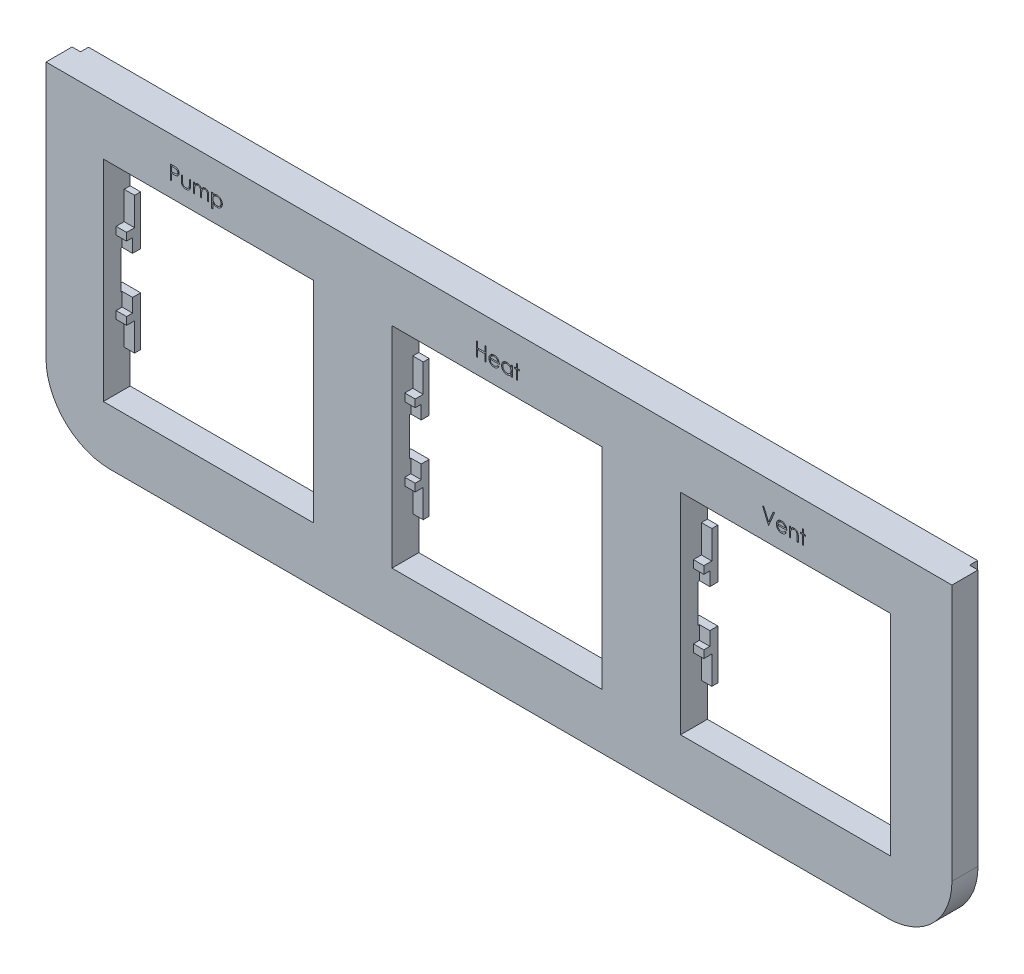
SolidWorks part; units mm, degrees
ref_plane "Спереди" through (0, 0, 0) normal (0, 0, 1) x (1, 0, 0)
ref_plane "Сверху" through (0, 0, 0) normal (0, 1, 0) x (1, 0, 0)
ref_plane "Справа" through (0, 0, 0) normal (1, 0, 0) x (0, 0, -1)
sketch "Эскиз1" plane through (0, 0, 0) normal (0, 0, 1) x (1, 0, 0)
  line L1 (0, 0) -> (226, 0)
  line L2 (0, 0) -> (0, 80)
  line L3 (0, 80) -> (226, 80)
  line L4 (226, 0) -> (226, 80)
  dimension "D1" = 80
  dimension "D2" = 226
extrude "Бобышка-Вытянуть1" add sketch "Эскиз1" along normal blind 6.5
sketch "Эскиз2" plane through (0, 0, 0) normal (0, 0, -1) x (-1, 0, 0)
  line L0 (-226, 80) -> (0, 80) construction
  line L1 (-223.9, 80) -> (-2.1, 80)
  line L2 (-223.9, 80) -> (-223.9, 2.1)
  line L3 (-223.9, 2.1) -> (-2.1, 2.1)
  line L4 (-2.1, 80) -> (-2.1, 2.1)
  dimension "D1" = 2.1
  dimension "D2" = 2.1
  dimension "D3" = 2.1
extrude "Бобышка-Вытянуть2" add sketch "Эскиз2" along normal blind 2
sketch "Эскиз3" plane through (0, 0, 6.5) normal (0, 0, 1) x (1, 0, 0)
  line L0 (0, 80) -> (0, 0) construction
  line L1 (66.7, 66.2) -> (14.3, 13.8) construction
  line L2 (14.3, 66.2) -> (66.7, 66.2)
  line L3 (14.3, 66.2) -> (14.3, 13.8)
  line L4 (14.3, 13.8) -> (66.7, 13.8)
  line L5 (66.7, 66.2) -> (66.7, 13.8)
  line L6 (86.3, 66.2) -> (138.7, 66.2)
  line L7 (86.3, 66.2) -> (86.3, 13.8)
  line L8 (86.3, 13.8) -> (138.7, 13.8)
  line L9 (138.7, 66.2) -> (138.7, 13.8)
  line L10 (158.3, 66.2) -> (210.7, 66.2)
  line L11 (158.3, 66.2) -> (158.3, 13.8)
  line L12 (158.3, 13.8) -> (210.7, 13.8)
  line L13 (210.7, 66.2) -> (210.7, 13.8)
  point P0 (40.5, 40)
  point P8 (40.5, 40)
  dimension "D1" = 40
  dimension "D2" = 40.5
  dimension "D3" = 52.4
  dimension "D4" = 52.4
  dimension "D5" = 3
extrude "Вырез-Вытянуть1" cut sketch "Эскиз3" against normal through all
sketch "Эскиз4" plane through (0, 0, -2) normal (0, 0, -1) x (-1, 0, 0)
  line L1 (-221.9, 76) -> (-4.1, 76)
  line L2 (-221.9, 76) -> (-221.9, 4.1)
  line L3 (-221.9, 4.1) -> (-4.1, 4.1)
  line L4 (-4.1, 76) -> (-4.1, 4.1)
  dimension "D1" = 2
  dimension "D2" = 2
  dimension "D3" = 2
  dimension "D4" = 4
extrude "Вырез-Вытянуть2" cut sketch "Эскиз4" against normal offset from surface (5.5 mm away) 3 up to face at (40.5, 40, 6.5)
sketch "Эскиз5" plane through (0, 0, 3.5) normal (0, 0, -1) x (-1, 0, 0)
  line L0 (-158.3, 13.8) -> (-210.7, 13.8) construction
  line L1 (-158.3, 66.2) -> (-158.3, 13.8) construction
  line L2 (-210.7, 66.2) -> (-158.3, 66.2) construction
  line L3 (-210.7, 13.8) -> (-210.7, 66.2) construction
  line L4 (-158.3, 13.8) -> (-210.7, 13.8)
  line L5 (-158.3, 66.2) -> (-158.3, 13.8)
  line L6 (-210.7, 66.2) -> (-158.3, 66.2)
  line L7 (-210.7, 13.8) -> (-210.7, 66.2)
  line L8 (-86.3, 13.8) -> (-138.7, 13.8)
  line L9 (-212.7, 68.2) -> (-156.3, 68.2)
  line L10 (-212.7, 68.2) -> (-212.7, 11.8)
  line L11 (-212.7, 11.8) -> (-156.3, 11.8)
  line L12 (-156.3, 68.2) -> (-156.3, 11.8)
  line L13 (-86.3, 66.2) -> (-86.3, 13.8)
  line L14 (-138.7, 66.2) -> (-86.3, 66.2)
  line L15 (-138.7, 13.8) -> (-138.7, 66.2)
  line L16 (-140.7, 68.2) -> (-84.3, 68.2)
  line L17 (-140.7, 68.2) -> (-140.7, 11.8)
  line L18 (-140.7, 11.8) -> (-84.3, 11.8)
  line L19 (-84.3, 68.2) -> (-84.3, 11.8)
  line L20 (-14.3, 13.8) -> (-66.7, 13.8)
  line L21 (-14.3, 66.2) -> (-14.3, 13.8)
  line L22 (-66.7, 66.2) -> (-14.3, 66.2)
  line L23 (-66.7, 13.8) -> (-66.7, 66.2)
  line L24 (-68.7, 68.2) -> (-12.3, 68.2)
  line L25 (-68.7, 68.2) -> (-68.7, 11.8)
  line L26 (-68.7, 11.8) -> (-12.3, 11.8)
  line L27 (-12.3, 68.2) -> (-12.3, 11.8)
  dimension "D1" = 2
  dimension "D2" = 2
  dimension "D3" = 2
  dimension "D4" = 2
  dimension "D5" = 3
extrude "Бобышка-Вытянуть3" add sketch "Эскиз5" along normal blind 6.7 from surface at -3 starting at face at (40.5, 40, 6.5)
sketch "Эскиз6" plane through (0, 0, -0.2) normal (0, 0, -1) x (-1, 0, 0)
  line L0 (-210.7, 40) -> (-158.3, 40) construction
  line L1 (-210.7, 13.8) -> (-210.7, 66.2) construction
  line L2 (-158.3, 66.2) -> (-158.3, 13.8) construction
  line L3 (-208.1, 22.95) -> (-208.1, 35.25)
  line L4 (-208.1, 35.25) -> (-208.1, 44.75) construction
  line L5 (-208.1, 44.75) -> (-208.1, 57.05)
  line L6 (-210.7, 66.2) -> (-158.3, 66.2) construction
  line L7 (-208.1, 44.75) -> (-210.7, 44.75)
  line L8 (-210.7, 44.75) -> (-210.7, 57.05)
  line L9 (-210.7, 57.05) -> (-208.1, 57.05)
  line L10 (-208.1, 35.25) -> (-210.7, 35.25)
  line L11 (-210.7, 35.25) -> (-210.7, 22.95)
  line L12 (-210.7, 22.95) -> (-208.1, 22.95)
  line L13 (-184.5, 40) -> (-184.5, 13.8) construction
  line L14 (-158.3, 13.8) -> (-210.7, 13.8) construction
  line L15 (-158.3, 22.95) -> (-160.9, 22.95)
  line L16 (-158.3, 35.25) -> (-158.3, 22.95)
  line L17 (-160.9, 35.25) -> (-158.3, 35.25)
  line L18 (-158.3, 57.05) -> (-160.9, 57.05)
  line L19 (-158.3, 44.75) -> (-158.3, 57.05)
  line L20 (-160.9, 44.75) -> (-158.3, 44.75)
  line L21 (-160.9, 44.75) -> (-160.9, 57.05)
  line L22 (-160.9, 22.95) -> (-160.9, 35.25)
  line L23 (-136.1, 22.95) -> (-136.1, 35.25)
  line L24 (-136.1, 44.75) -> (-136.1, 57.05)
  line L25 (-136.1, 44.75) -> (-138.7, 44.75)
  line L26 (-138.7, 44.75) -> (-138.7, 57.05)
  line L27 (-138.7, 57.05) -> (-136.1, 57.05)
  line L28 (-136.1, 35.25) -> (-138.7, 35.25)
  line L29 (-138.7, 35.25) -> (-138.7, 22.95)
  line L30 (-138.7, 22.95) -> (-136.1, 22.95)
  line L31 (-86.3, 22.95) -> (-88.9, 22.95)
  line L32 (-86.3, 35.25) -> (-86.3, 22.95)
  line L33 (-88.9, 35.25) -> (-86.3, 35.25)
  line L34 (-86.3, 57.05) -> (-88.9, 57.05)
  line L35 (-86.3, 44.75) -> (-86.3, 57.05)
  line L36 (-88.9, 44.75) -> (-86.3, 44.75)
  line L37 (-88.9, 44.75) -> (-88.9, 57.05)
  line L38 (-88.9, 22.95) -> (-88.9, 35.25)
  line L39 (-136.1, 35.25) -> (-136.1, 44.75) construction
  line L40 (-64.1, 22.95) -> (-64.1, 35.25)
  line L41 (-64.1, 44.75) -> (-64.1, 57.05)
  line L42 (-64.1, 44.75) -> (-66.7, 44.75)
  line L43 (-66.7, 44.75) -> (-66.7, 57.05)
  line L44 (-66.7, 57.05) -> (-64.1, 57.05)
  line L45 (-64.1, 35.25) -> (-66.7, 35.25)
  line L46 (-66.7, 35.25) -> (-66.7, 22.95)
  line L47 (-66.7, 22.95) -> (-64.1, 22.95)
  line L48 (-14.3, 22.95) -> (-16.9, 22.95)
  line L49 (-14.3, 35.25) -> (-14.3, 22.95)
  line L50 (-16.9, 35.25) -> (-14.3, 35.25)
  line L51 (-14.3, 57.05) -> (-16.9, 57.05)
  line L52 (-14.3, 44.75) -> (-14.3, 57.05)
  line L53 (-16.9, 44.75) -> (-14.3, 44.75)
  line L54 (-16.9, 44.75) -> (-16.9, 57.05)
  line L55 (-16.9, 22.95) -> (-16.9, 35.25)
  line L56 (-64.1, 35.25) -> (-64.1, 44.75) construction
  point P13 (-208.1, 40)
  dimension "D1" = 9.15
  dimension "D2" = 9.15
  dimension "D3" = 9.5
  dimension "D4" = 2.6
  dimension "D5" = 3
extrude "Бобышка-Вытянуть4" add sketch "Эскиз6" against normal blind 1.5
sketch "Эскиз7" plane through (0, 0, 1.3) normal (0, 0, 1) x (1, 0, 0)
  line L0 (210.7, 13.8) -> (210.7, 66.2) construction
  line L1 (208.1, 44.75) -> (210.7, 44.75)
  line L2 (208.1, 44.75) -> (208.1, 50.05)
  line L3 (208.1, 50.05) -> (210.7, 50.05)
  line L4 (210.7, 44.75) -> (210.7, 50.05)
  line L5 (210.7, 35.25) -> (210.7, 22.95) construction
  line L6 (208.1, 35.25) -> (210.7, 35.25)
  line L7 (208.1, 35.25) -> (208.1, 29.95)
  line L8 (208.1, 29.95) -> (210.7, 29.95)
  line L9 (210.7, 35.25) -> (210.7, 29.95)
  line L10 (158.3, 22.95) -> (158.3, 35.25) construction
  line L11 (160.9, 35.25) -> (158.3, 35.25)
  line L12 (160.9, 35.25) -> (160.9, 29.95)
  line L13 (160.9, 29.95) -> (158.3, 29.95)
  line L14 (158.3, 35.25) -> (158.3, 29.95)
  line L15 (158.3, 44.75) -> (158.3, 57.05) construction
  line L16 (160.9, 44.75) -> (158.3, 44.75)
  line L17 (160.9, 44.75) -> (160.9, 50.05)
  line L18 (160.9, 50.05) -> (158.3, 50.05)
  line L19 (158.3, 44.75) -> (158.3, 50.05)
  line L20 (136.1, 44.75) -> (138.7, 44.75)
  line L21 (136.1, 44.75) -> (136.1, 50.05)
  line L22 (136.1, 50.05) -> (138.7, 50.05)
  line L23 (138.7, 44.75) -> (138.7, 50.05)
  line L24 (136.1, 35.25) -> (138.7, 35.25)
  line L25 (136.1, 35.25) -> (136.1, 29.95)
  line L26 (136.1, 29.95) -> (138.7, 29.95)
  line L27 (138.7, 35.25) -> (138.7, 29.95)
  line L28 (88.9, 35.25) -> (86.3, 35.25)
  line L29 (88.9, 35.25) -> (88.9, 29.95)
  line L30 (88.9, 29.95) -> (86.3, 29.95)
  line L31 (86.3, 35.25) -> (86.3, 29.95)
  line L32 (88.9, 44.75) -> (86.3, 44.75)
  line L33 (88.9, 44.75) -> (88.9, 50.05)
  line L34 (88.9, 50.05) -> (86.3, 50.05)
  line L35 (86.3, 44.75) -> (86.3, 50.05)
  line L36 (64.1, 44.75) -> (66.7, 44.75)
  line L37 (64.1, 44.75) -> (64.1, 50.05)
  line L38 (64.1, 50.05) -> (66.7, 50.05)
  line L39 (66.7, 44.75) -> (66.7, 50.05)
  line L40 (64.1, 35.25) -> (66.7, 35.25)
  line L41 (64.1, 35.25) -> (64.1, 29.95)
  line L42 (64.1, 29.95) -> (66.7, 29.95)
  line L43 (66.7, 35.25) -> (66.7, 29.95)
  line L44 (16.9, 35.25) -> (14.3, 35.25)
  line L45 (16.9, 35.25) -> (16.9, 29.95)
  line L46 (16.9, 29.95) -> (14.3, 29.95)
  line L47 (14.3, 35.25) -> (14.3, 29.95)
  line L48 (16.9, 44.75) -> (14.3, 44.75)
  line L49 (16.9, 44.75) -> (16.9, 50.05)
  line L50 (16.9, 50.05) -> (14.3, 50.05)
  line L51 (14.3, 44.75) -> (14.3, 50.05)
  dimension "D1" = 5.3
  dimension "D2" = 5.3
  dimension "D3" = 5.3
  dimension "D4" = 5.3
  dimension "D5" = 3
extrude "Бобышка-Вытянуть5" add sketch "Эскиз7" along normal blind 2 from surface at -1.5 starting at face at (112.5, 40, -0.2)
sketch "Эскиз8" plane through (0, 0, 1.8) normal (0, 0, 1) x (1, 0, 0)
  line L0 (210.7, 35.25) -> (210.7, 29.95) construction
  line L1 (208.1, 29.95) -> (210.7, 29.95)
  line L2 (208.1, 29.95) -> (208.1, 31.85)
  line L3 (208.1, 31.85) -> (210.7, 31.85)
  line L4 (210.7, 29.95) -> (210.7, 31.85)
  line L5 (210.7, 50.05) -> (210.7, 44.75) construction
  line L6 (208.1, 50.05) -> (210.7, 50.05)
  line L7 (208.1, 50.05) -> (208.1, 48.15)
  line L8 (208.1, 48.15) -> (210.7, 48.15)
  line L9 (210.7, 50.05) -> (210.7, 48.15)
  line L10 (158.3, 29.95) -> (158.3, 35.25) construction
  line L11 (160.9, 29.95) -> (158.3, 29.95)
  line L12 (160.9, 29.95) -> (160.9, 31.85)
  line L13 (160.9, 31.85) -> (158.3, 31.85)
  line L14 (158.3, 29.95) -> (158.3, 31.85)
  line L15 (158.3, 66.2) -> (158.3, 13.8) construction
  line L16 (160.9, 50.05) -> (158.3, 50.05)
  line L17 (160.9, 50.05) -> (160.9, 48.15)
  line L18 (160.9, 48.15) -> (158.3, 48.15)
  line L19 (158.3, 50.05) -> (158.3, 48.15)
  line L20 (136.1, 29.95) -> (138.7, 29.95)
  line L21 (136.1, 29.95) -> (136.1, 31.85)
  line L22 (136.1, 31.85) -> (138.7, 31.85)
  line L23 (138.7, 29.95) -> (138.7, 31.85)
  line L24 (136.1, 50.05) -> (138.7, 50.05)
  line L25 (136.1, 50.05) -> (136.1, 48.15)
  line L26 (136.1, 48.15) -> (138.7, 48.15)
  line L27 (138.7, 50.05) -> (138.7, 48.15)
  line L28 (88.9, 29.95) -> (86.3, 29.95)
  line L29 (88.9, 29.95) -> (88.9, 31.85)
  line L30 (88.9, 31.85) -> (86.3, 31.85)
  line L31 (86.3, 29.95) -> (86.3, 31.85)
  line L32 (88.9, 50.05) -> (86.3, 50.05)
  line L33 (88.9, 50.05) -> (88.9, 48.15)
  line L34 (88.9, 48.15) -> (86.3, 48.15)
  line L35 (86.3, 50.05) -> (86.3, 48.15)
  line L36 (64.1, 29.95) -> (66.7, 29.95)
  line L37 (64.1, 29.95) -> (64.1, 31.85)
  line L38 (64.1, 31.85) -> (66.7, 31.85)
  line L39 (66.7, 29.95) -> (66.7, 31.85)
  line L40 (64.1, 50.05) -> (66.7, 50.05)
  line L41 (64.1, 50.05) -> (64.1, 48.15)
  line L42 (64.1, 48.15) -> (66.7, 48.15)
  line L43 (66.7, 50.05) -> (66.7, 48.15)
  line L44 (16.9, 29.95) -> (14.3, 29.95)
  line L45 (16.9, 29.95) -> (16.9, 31.85)
  line L46 (16.9, 31.85) -> (14.3, 31.85)
  line L47 (14.3, 29.95) -> (14.3, 31.85)
  line L48 (16.9, 50.05) -> (14.3, 50.05)
  line L49 (16.9, 50.05) -> (16.9, 48.15)
  line L50 (16.9, 48.15) -> (14.3, 48.15)
  line L51 (14.3, 50.05) -> (14.3, 48.15)
  dimension "D1" = 1.9
  dimension "D2" = 1.9
  dimension "D3" = 1.9
  dimension "D4" = 1.9
  dimension "D5" = 3
extrude "Бобышка-Вытянуть6" add sketch "Эскиз8" along normal blind 3.5 from surface at -2 starting at face at (184.5, 40, -0.2)
sketch "Эскиз9" plane through (0, 0, -0.2) normal (0, 0, -1) x (-1, 0, 0)
  line L0 (-12.3, 68.2) -> (-12.3, 11.8) construction
  line L1 (-12.3, 35.25) -> (-212.7, 35.25)
  line L2 (-12.3, 35.25) -> (-12.3, 44.75)
  line L3 (-12.3, 44.75) -> (-212.7, 44.75)
  line L4 (-212.7, 35.25) -> (-212.7, 44.75)
  line L5 (-212.7, 68.2) -> (-212.7, 11.8) construction
extrude "Вырез-Вытянуть3" cut sketch "Эскиз9" against normal blind 2.3
fillet "Скругление1" radius 15 4 edges at (2.1, 2.1, -1) (4.1, 4.1, 0.75) (223.9, 2.1, -1) (221.9, 4.1, 0.75)
fillet "Скругление2" radius 16 2 edges at (226, 0, 3.25) (0, 0, 3.25)
sketch "Эскиз10" plane through (0, 0, 6.5) normal (0, 0, 1) x (1, 0, 0)
  line L0 (226, 70) -> (0, 70) construction
  line L1 (226, 16) -> (226, 80) construction
  line L2 (0, 80) -> (0, 16) construction
  text T0 "Vent                           "
  text T1 "Heat                                                                                "
  text T2 "Pump                                                                                                                                       "
  point P4 (0, 0)
  dimension "D1" = 10
extrude "Вырез-Вытянуть4" cut sketch "Эскиз10" against normal blind 0.6
